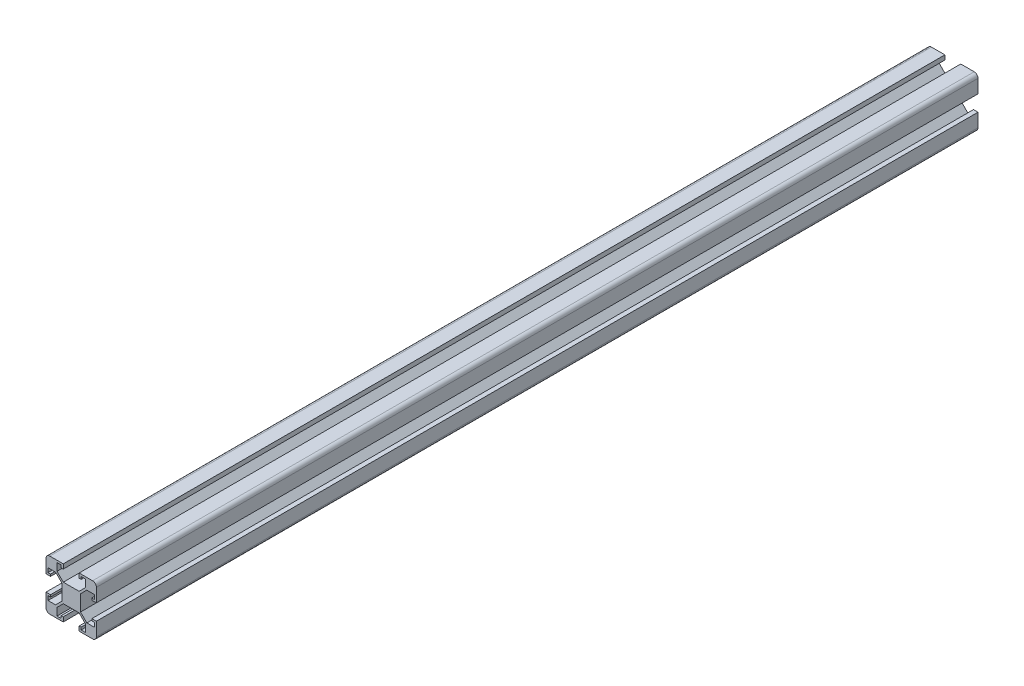
SolidWorks part; units mm, degrees
ref_plane "前视基准面" through (0, 0, 0) normal (0, 0, 1) x (1, 0, 0)
ref_plane "上视基准面" through (0, 0, 0) normal (0, 1, 0) x (1, 0, 0)
ref_plane "右视基准面" through (0, 0, 0) normal (1, 0, 0) x (0, 0, -1)
other "Configuration Table"
sketch "草图1" plane through (0, 0, 0) normal (0, 0, 1) x (1, 0, 0)
  line L0 (-10, 0) -> (10, 0) construction
  line L1 (-10, -10) -> (10, -10)
  line L2 (-10, -10) -> (-10, 10)
  line L3 (-10, 10) -> (10, 10)
  line L4 (10, -10) -> (10, 10)
  line L5 (-10, -10) -> (10, 10) construction
  line L6 (-10, 10) -> (10, -10) construction
  line L7 (0, 10) -> (0, -10) construction
  line L8 (-3.15, 10) -> (-3.15, 8.2)
  line L9 (-3.15, 8.2) -> (-3.95, 8.2)
  line L10 (-3.95, 8.2) -> (-3.95, 9.2)
  line L11 (-3.95, 9.2) -> (-5.6343, 9.2)
  line L12 (-5.6343, 9.2) -> (-5.6343, 6.2)
  line L13 (-5.6343, 6.2) -> (-3.1343, 3.7)
  line L14 (-3.1343, 3.7) -> (3.1343, 3.7)
  line L15 (5.6343, 6.2) -> (3.1343, 3.7)
  line L16 (5.6343, 9.2) -> (5.6343, 6.2)
  line L17 (3.95, 9.2) -> (5.6343, 9.2)
  line L18 (3.95, 8.2) -> (3.95, 9.2)
  line L19 (3.15, 8.2) -> (3.95, 8.2)
  line L20 (3.15, 10) -> (3.15, 8.2)
  line L21 (3.15, -10) -> (3.15, -8.2)
  line L22 (3.15, -8.2) -> (3.95, -8.2)
  line L23 (3.95, -8.2) -> (3.95, -9.2)
  line L24 (5.6343, -9.2) -> (5.6343, -6.2)
  line L25 (5.6343, -6.2) -> (3.1343, -3.7)
  line L26 (-3.1343, -3.7) -> (3.1343, -3.7)
  line L27 (-5.6343, -6.2) -> (-3.1343, -3.7)
  line L28 (-5.6343, -9.2) -> (-5.6343, -6.2)
  line L29 (-3.95, -9.2) -> (-5.6343, -9.2)
  line L30 (-3.95, -8.2) -> (-3.95, -9.2)
  line L31 (-3.15, -8.2) -> (-3.95, -8.2)
  line L32 (-3.15, -10) -> (-3.15, -8.2)
  line L33 (-6.2, 5.6343) -> (-3.7, 3.1343)
  line L34 (-9.2, 5.6343) -> (-6.2, 5.6343)
  line L35 (-9.2, 3.95) -> (-9.2, 5.6343)
  line L36 (-8.2, 3.95) -> (-9.2, 3.95)
  line L37 (-8.2, 3.15) -> (-8.2, 3.95)
  line L38 (-10, 3.15) -> (-8.2, 3.15)
  line L39 (-3.7, 3.1343) -> (-3.7, -3.1343)
  line L40 (-10, -3.15) -> (-8.2, -3.15)
  line L41 (-8.2, -3.15) -> (-8.2, -3.95)
  line L42 (-8.2, -3.95) -> (-9.2, -3.95)
  line L43 (-9.2, -3.95) -> (-9.2, -5.6343)
  line L44 (-9.2, -5.6343) -> (-6.2, -5.6343)
  line L45 (-6.2, -5.6343) -> (-3.7, -3.1343)
  line L46 (10, -3.15) -> (8.2, -3.15)
  line L47 (8.2, -3.15) -> (8.2, -3.95)
  line L48 (8.2, -3.95) -> (9.2, -3.95)
  line L49 (9.2, -3.95) -> (9.2, -5.6343)
  line L50 (9.2, -5.6343) -> (6.2, -5.6343)
  line L51 (6.2, -5.6343) -> (3.7, -3.1343)
  line L52 (3.7, -3.1343) -> (3.7, 3.1343)
  line L53 (6.2, 5.6343) -> (3.7, 3.1343)
  line L54 (9.2, 5.6343) -> (6.2, 5.6343)
  line L55 (9.2, 3.95) -> (9.2, 5.6343)
  line L56 (8.2, 3.95) -> (9.2, 3.95)
  line L57 (8.2, 3.15) -> (8.2, 3.95)
  line L58 (10, 3.15) -> (8.2, 3.15)
  line L59 (3.95, -9.2) -> (5.6343, -9.2)
  point P0 (0, 0)
  point P19 (0, 3.7)
  dimension "D1" = 20
  dimension "D2" = 20
  dimension "D3" = 6.85
  dimension "D4" = 1.8
  dimension "D5" = 0.8
  dimension "D6" = 1
  dimension "D7" = 6.3
  dimension "D8" = 0.4
  dimension "D9" = 3
extrude "凸台-拉伸2" add sketch "草图1" along normal blind 350 contours L59 L23 L22 L21 L1 L4 L46 L47 L48 L49 L50 L51 L52 L53 L54 L55 L56 L57 L58 L3 L20 L19 L18 L17 L16 L15 L14 L13 L12 L11 L10 L9 L8 L2 L38 L37 L36 L35 L34 L33 L39 L45 L44 L43 L42 L41 L40
fillet "圆角1" radius 1.5 4 edges at (10, 10, 175) (10, -10, 175) (-10, -10, 175) (-10, 10, 175)
